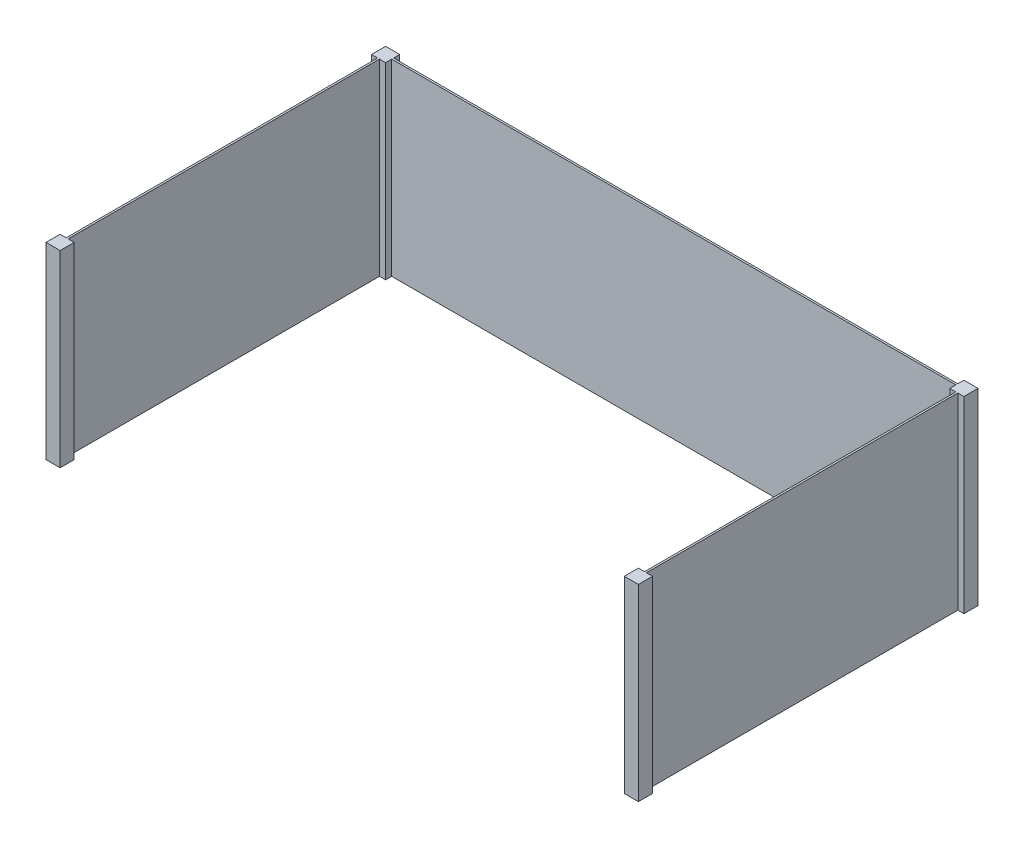
SolidWorks part; units mm, degrees
ref_plane "Front Plane" through (0, 0, 0) normal (0, 0, 1) x (1, 0, 0)
ref_plane "Top Plane" through (0, 0, 0) normal (0, 1, 0) x (1, 0, 0)
ref_plane "Right Plane" through (0, 0, 0) normal (1, 0, 0) x (0, 0, -1)
sketch "Sketch1" plane through (0, 0, 0) normal (0, 1, 0) x (1, 0, 0)
  line L0 (3035.9725, 37.5) -> (3110.9725, -37.5) construction
  line L1 (-37.5, 37.5) -> (37.5, 37.5)
  line L2 (-37.5, 37.5) -> (-37.5, -37.5)
  line L3 (-37.5, -37.5) -> (-5, -37.5)
  line L4 (37.5, 37.5) -> (37.5, 5)
  line L5 (-37.5, 37.5) -> (37.5, -37.5) construction
  line L6 (-37.5, -37.5) -> (37.5, 37.5) construction
  line L7 (3035.9725, -37.5) -> (3110.9725, 37.5) construction
  line L8 (-5, -37.5) -> (-5, -1692.394)
  line L9 (5, -1692.394) -> (5, -37.5)
  line L10 (37.5, 5) -> (3035.9725, 5)
  line L11 (-37.5, -1767.394) -> (37.5, -1692.394) construction
  line L12 (-37.5, -1692.394) -> (-5, -1692.394)
  line L17 (-37.5, -1692.394) -> (-37.5, -1767.394)
  line L18 (-37.5, -1767.394) -> (37.5, -1767.394)
  line L19 (3035.9725, -1692.394) -> (3068.4725, -1692.394)
  line L20 (3035.9725, -1692.394) -> (3035.9725, -1767.394)
  line L21 (3035.9725, -1767.394) -> (3110.9725, -1767.394)
  line L22 (3110.9725, -1692.394) -> (3110.9725, -1767.394)
  line L23 (3035.9725, -1692.394) -> (3110.9725, -1767.394) construction
  line L24 (3035.9725, -1767.394) -> (3110.9725, -1692.394) construction
  line L25 (3035.9725, 37.5) -> (3110.9725, 37.5)
  line L26 (3035.9725, 37.5) -> (3035.9725, 5)
  line L27 (3035.9725, -37.5) -> (3068.4725, -37.5)
  line L28 (3110.9725, 37.5) -> (3110.9725, -37.5)
  line L29 (3035.9725, 37.5) -> (3110.9725, -37.5) construction
  line L30 (3035.9725, -37.5) -> (3110.9725, 37.5) construction
  line L31 (-37.5, -1692.394) -> (37.5, -1767.394) construction
  line L32 (37.5, -1692.394) -> (37.5, -1767.394)
  line L33 (-37.5, -1692.394) -> (37.5, -1767.394) construction
  line L34 (-37.5, -1767.394) -> (37.5, -1692.394) construction
  line L35 (3035.9725, -1692.394) -> (3110.9725, -1767.394) construction
  line L36 (3035.9725, -1767.394) -> (3110.9725, -1692.394) construction
  line L37 (3078.4725, -37.5) -> (3078.4725, -1692.394)
  line L38 (3068.4725, -1692.394) -> (3068.4725, -37.5)
  line L39 (3035.9725, -5) -> (37.5, -5)
  line L40 (5, -1692.394) -> (37.5, -1692.394)
  line L41 (5, -37.5) -> (37.5, -37.5)
  line L42 (37.5, -5) -> (37.5, -37.5)
  line L43 (3078.4725, -37.5) -> (3110.9725, -37.5)
  line L44 (3035.9725, -5) -> (3035.9725, -37.5)
  line L45 (3078.4725, -1692.394) -> (3110.9725, -1692.394)
  point P0 (0, 0)
  point P6 (0, -1729.894)
  point P7 (0, -1729.894)
  point P9 (3073.4725, 0)
  point P14 (3073.4725, -1729.894)
  point P19 (0, -1729.894)
  point P26 (3073.4725, -1729.894)
  point P31 (3073.4725, 0)
  point P35 (0, -1729.894)
  point P42 (2673.4725, -1729.894)
  point P45 (3078.9845, -1723.6782)
  point P46 (0, 0)
  point P47 (3073.4725, -1729.894)
  dimension "D2" = 75
  dimension "D3" = 75
  dimension "D5" = 3073.4725
  dimension "D6" = 5
  dimension "D7" = 5
  dimension "D4" = 2
  dimension "D1" = 2
extrude "Boss-Extrude1" add sketch "Sketch1" along normal blind 1000
